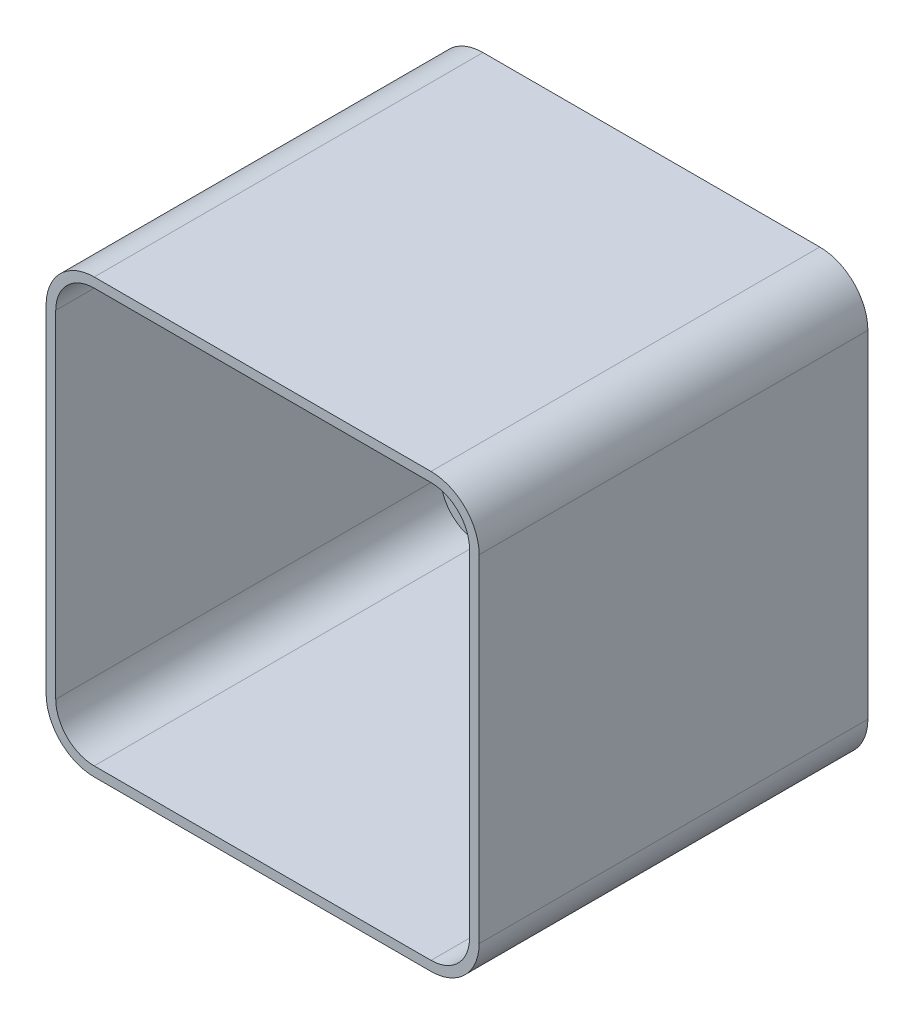
SolidWorks part; units mm, degrees
material "ABS"
ref_plane "Front Plane" through (0, 0, 0) normal (0, 0, 1) x (1, 0, 0)
ref_plane "Top Plane" through (0, 0, 0) normal (0, 1, 0) x (1, 0, 0)
ref_plane "Right Plane" through (0, 0, 0) normal (1, 0, 0) x (0, 0, -1)
sketch "Sketch1" plane through (0, 0, 0) normal (0, 0, 1) x (1, 0, 0)
  line L1 (-175, 225) -> (175, 225)
  line L2 (-225, 175) -> (-225, -175)
  line L3 (-175, -225) -> (175, -225)
  line L4 (225, 175) -> (225, -175)
  line L5 (-225, 225) -> (225, -225) construction
  line L6 (-225, -225) -> (225, 225) construction
  arc A0 (175, 225) -> (225, 175) centre (175, 175) cw
  arc A1 (175, -225) -> (225, -175) centre (175, -175) ccw
  arc A2 (-225, -175) -> (-175, -225) centre (-175, -175) ccw
  arc A3 (-175, 225) -> (-225, 175) centre (-175, 175) ccw
  point P0 (0, 0)
  dimension "D3" = 50
  dimension "D1" = 450
  dimension "D2" = 450
extrude "Boss-Extrude1" add sketch "Sketch1" along normal blind 4
sketch "Sketch2" plane through (0, 0, 4) normal (0, 0, 1) x (1, 0, 0)
  line L0 (-215, 175) -> (-215, -175)
  line L1 (-175, -215) -> (175, -215)
  line L2 (215, -175) -> (215, 175)
  line L3 (175, 215) -> (-175, 215)
  line L4 (175, 225) -> (-175, 225)
  line L5 (-225, 175) -> (-225, -175)
  line L6 (-175, -225) -> (175, -225)
  line L7 (225, -175) -> (225, 175)
  line L8 (175, 225) -> (-175, 225)
  line L9 (-225, 175) -> (-225, -175)
  line L10 (-175, -225) -> (175, -225)
  line L11 (225, -175) -> (225, 175)
  arc A0 (-215, -175) -> (-175, -215) centre (-175, -175) ccw
  arc A1 (175, -215) -> (215, -175) centre (175, -175) ccw
  arc A2 (215, 175) -> (175, 215) centre (175, 175) ccw
  arc A3 (-175, 215) -> (-215, 175) centre (-175, 175) ccw
  arc A4 (225, 175) -> (175, 225) centre (175, 175) ccw
  arc A5 (-175, 225) -> (-225, 175) centre (-175, 175) ccw
  arc A6 (-225, -175) -> (-175, -225) centre (-175, -175) ccw
  arc A7 (175, -225) -> (225, -175) centre (175, -175) ccw
  arc A8 (225, 175) -> (175, 225) centre (175, 175) ccw
  arc A9 (-175, 225) -> (-225, 175) centre (-175, 175) ccw
  arc A10 (-225, -175) -> (-175, -225) centre (-175, -175) ccw
  arc A11 (175, -225) -> (225, -175) centre (175, -175) ccw
  dimension "D1" = 0
  dimension "D2" = 10
extrude "Boss-Extrude2" add sketch "Sketch2" along normal blind 400
